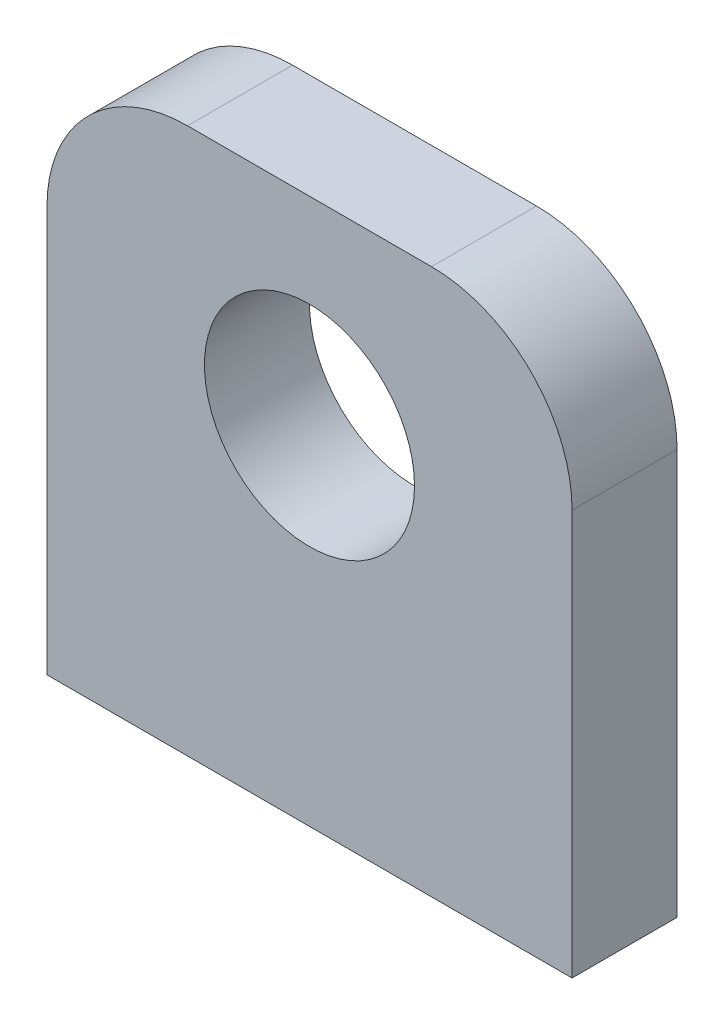
SolidWorks part; units mm, degrees
ref_plane "Alzado" through (0, 0, 0) normal (0, 0, 1) x (1, 0, 0)
ref_plane "Planta" through (0, 0, 0) normal (0, 1, 0) x (1, 0, 0)
ref_plane "Vista lateral" through (0, 0, 0) normal (1, 0, 0) x (0, 0, -1)
sketch "Croquis1" plane through (0, 0, 0) normal (0, 0, 1) x (1, 0, 0)
  line L0 (31.75, 66) -> (31.75, 42) construction
  line L1 (0, 0) -> (63.5, 0)
  line L2 (0, 0) -> (0, 66)
  line L3 (0, 66) -> (63.5, 66)
  line L4 (63.5, 0) -> (63.5, 66)
  circle A0 centre (31.75, 42) radius 12.7
  dimension "D4" = 25.4
  dimension "D1" = 63.5
  dimension "D2" = 66
  dimension "D3" = 24
extrude "Saliente-Extruir1" add sketch "Croquis1" along normal blind 12.7
fillet "Redondeo1" radius 17 2 edges at (63.5, 66, 6.35) (0, 66, 6.35)
